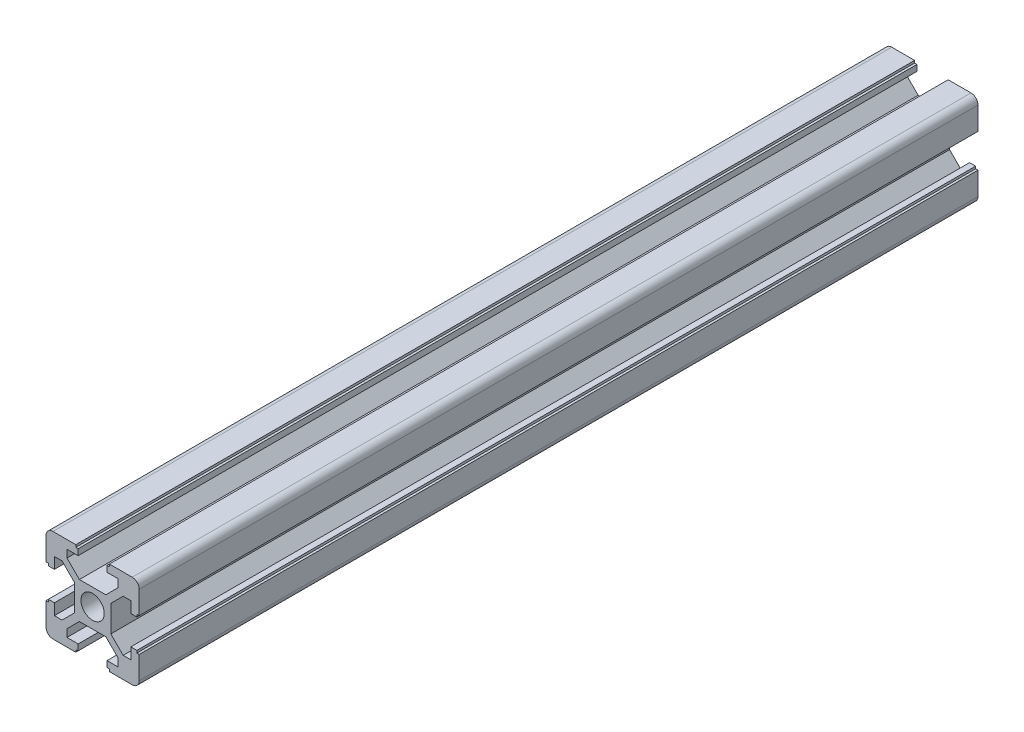
SolidWorks part; units mm, degrees
ref_plane "Front Plane" through (0, 0, 0) normal (0, 0, 1) x (1, 0, 0)
ref_plane "Top Plane" through (0, 0, 0) normal (0, 1, 0) x (1, 0, 0)
ref_plane "Right Plane" through (0, 0, 0) normal (1, 0, 0) x (0, 0, -1)
sketch "Sketch1" plane through (0, 0, 0) normal (0, 0, 1) x (1, 0, 0)
  line L0 (0, 13.3843) -> (0, -12.9126) construction
  line L1 (-14.4653, 0) -> (14.4653, 0) construction
  line L2 (2.8393, 3.9) -> (5.5, 6.5607)
  line L3 (-8.5, 10) -> (-3.6, 10)
  line L4 (-10, 8.5) -> (-10, 3.6)
  line L5 (-8.5, -10) -> (-3.6, -10)
  line L6 (10, 8.5) -> (10, 3.6)
  line L7 (-10, 10) -> (10, -10) construction
  line L8 (-10, -10) -> (10, 10) construction
  line L9 (-5.5, 8.2) -> (-3.1, 8.2)
  line L10 (-5.9626, 4.902) -> (-4.902, 5.9626) construction
  line L11 (-2.8393, 3.9) -> (-5.5, 6.5607)
  line L12 (-5.5, 8.2) -> (-5.5, 6.5607)
  line L13 (-2.8393, 3.9) -> (2.8393, 3.9)
  line L14 (5.5, 8.2) -> (5.5, 6.5607)
  line L15 (-3.1, 9.5) -> (-3.1, 8.2)
  line L16 (3.1, 9.5) -> (3.1, 8.2)
  line L17 (-3.1, 9.5) -> (3.1, 9.5) construction
  line L18 (-3.1, 9.5) -> (-3.6, 9.5)
  line L19 (-3.6, 9.5) -> (-3.6, 10)
  line L20 (3.1, 9.5) -> (3.6, 9.5)
  line L21 (3.6, 9.5) -> (3.6, 10)
  line L22 (3.6, 10) -> (8.5, 10)
  line L23 (3.1, 8.2) -> (5.5, 8.2)
  line L24 (-9.5, -3.1) -> (-9.5, -3.6)
  line L25 (-9.5, -3.6) -> (-10, -3.6)
  line L26 (-9.5, -3.1) -> (-8.2, -3.1)
  line L27 (-8.2, -3.1) -> (-8.2, -5.5)
  line L28 (-8.2, -5.5) -> (-6.5607, -5.5)
  line L29 (-3.9, -2.8393) -> (-6.5607, -5.5)
  line L30 (-3.9, 2.8393) -> (-3.9, -2.8393)
  line L31 (-3.9, 2.8393) -> (-6.5607, 5.5)
  line L32 (-8.2, 5.5) -> (-6.5607, 5.5)
  line L33 (-8.2, 5.5) -> (-8.2, 3.1)
  line L34 (-9.5, 3.1) -> (-8.2, 3.1)
  line L35 (-9.5, 3.1) -> (-9.5, 3.6)
  line L36 (-9.5, 3.6) -> (-10, 3.6)
  line L37 (-3.6, -9.5) -> (-3.6, -10)
  line L38 (-3.1, -9.5) -> (-3.6, -9.5)
  line L39 (-3.1, -9.5) -> (-3.1, -8.2)
  line L40 (-3.1, -8.2) -> (-5.5, -8.2)
  line L41 (-5.5, -8.2) -> (-5.5, -6.5607)
  line L42 (-2.8393, -3.9) -> (-5.5, -6.5607)
  line L43 (2.8393, -3.9) -> (-2.8393, -3.9)
  line L44 (2.8393, -3.9) -> (5.5, -6.5607)
  line L45 (5.5, -8.2) -> (5.5, -6.5607)
  line L46 (5.5, -8.2) -> (3.1, -8.2)
  line L47 (3.1, -9.5) -> (3.6, -9.5)
  line L48 (3.1, -9.5) -> (3.1, -8.2)
  line L49 (3.6, -9.5) -> (3.6, -10)
  line L50 (9.5, -3.6) -> (10, -3.6)
  line L51 (9.5, -3.1) -> (9.5, -3.6)
  line L52 (9.5, -3.1) -> (8.2, -3.1)
  line L53 (8.2, -5.5) -> (8.2, -3.1)
  line L54 (8.2, -5.5) -> (6.5607, -5.5)
  line L55 (3.9, -2.8393) -> (6.5607, -5.5)
  line L56 (3.9, -2.8393) -> (3.9, 2.8393)
  line L57 (3.9, 2.8393) -> (6.5607, 5.5)
  line L58 (8.2, 5.5) -> (6.5607, 5.5)
  line L59 (8.2, 3.1) -> (8.2, 5.5)
  line L60 (9.5, 3.1) -> (8.2, 3.1)
  line L61 (9.5, 3.1) -> (9.5, 3.6)
  line L62 (9.5, 3.6) -> (10, 3.6)
  line L63 (-10, -3.6) -> (-10, -8.5)
  line L64 (3.6, -10) -> (8.5, -10)
  line L65 (10, -3.6) -> (10, -8.5)
  arc A0 (8.5, 10) -> (10, 8.5) centre (8.5, 8.5) cw
  arc A1 (8.5, -10) -> (10, -8.5) centre (8.5, -8.5) ccw
  arc A2 (-10, -8.5) -> (-8.5, -10) centre (-8.5, -8.5) ccw
  arc A3 (-8.5, 10) -> (-10, 8.5) centre (-8.5, 8.5) ccw
  circle A4 centre (0, 0.2358) radius 2.5
  point P5 (0, 0)
  point P30 (-5.4323, 5.4323)
  point P38 (0, 9.5)
  dimension "D3" = 1.5
  dimension "D15" = 5
  dimension "D1" = 20
  dimension "D2" = 20
  dimension "D4" = 6.2
  dimension "D5" = 11
  dimension "D6" = 1.8
  dimension "D7" = 1.5
  dimension "D8" = 90
  dimension "D9" = 0.5
  dimension "D10" = 0.5
  dimension "D11" = 0.5
  dimension "D12" = 0.5
  dimension "D13" = 6.1
  dimension "D14" = 45
extrude "Boss-Extrude1" add sketch "Sketch1" along normal blind 180
